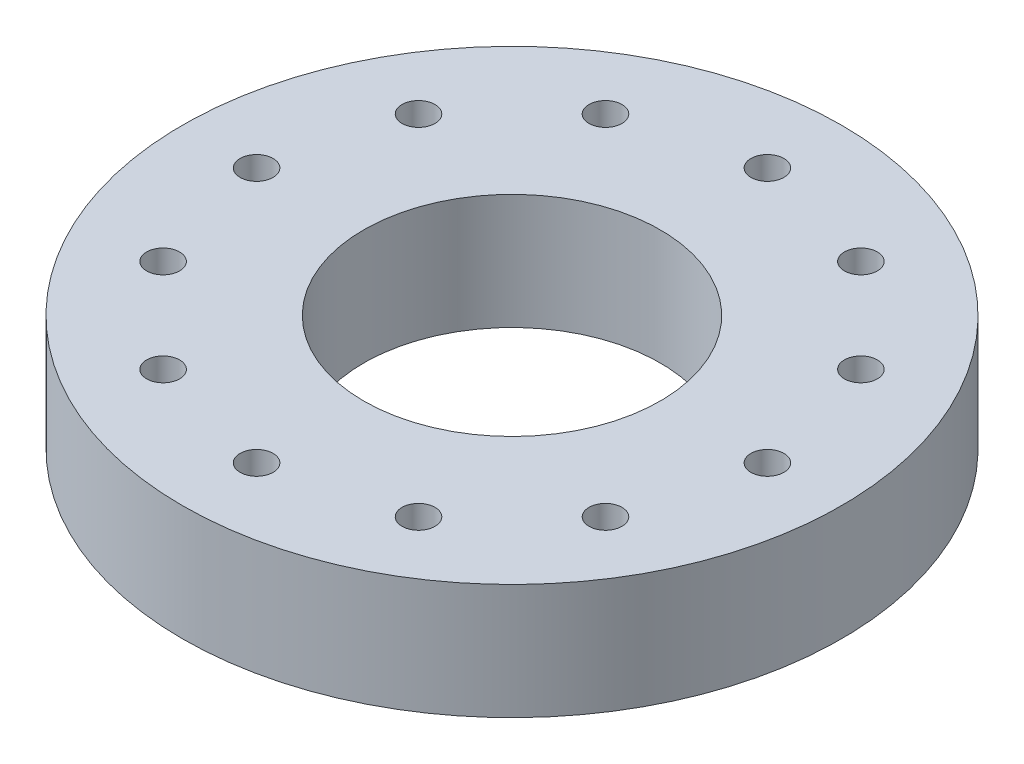
SolidWorks part; units mm, degrees
ref_plane "Front Plane" through (0, 0, 0) normal (0, 0, 1) x (1, 0, 0)
ref_plane "Top Plane" through (0, 0, 0) normal (0, 1, 0) x (1, 0, 0)
ref_plane "Right Plane" through (0, 0, 0) normal (1, 0, 0) x (0, 0, -1)
sketch "Sketch1" plane through (0, 0, 0) normal (0, 1, 0) x (1, 0, 0)
  circle A0 centre (0, 0) radius 20
  circle A1 centre (0, 0) radius 9
  circle A2 centre (0, 0) radius 15.5 construction
  circle A3 centre (0, 15.5) radius 1
  circle A4 centre (7.75, 13.4234) radius 1
  circle A5 centre (13.4234, 7.75) radius 1
  circle A6 centre (15.5, 0) radius 1
  circle A7 centre (13.4234, -7.75) radius 1
  circle A8 centre (7.75, -13.4234) radius 1
  circle A9 centre (0, -15.5) radius 1
  circle A10 centre (-7.75, -13.4234) radius 1
  circle A11 centre (-13.4234, -7.75) radius 1
  circle A12 centre (-15.5, 0) radius 1
  circle A13 centre (-13.4234, 7.75) radius 1
  circle A14 centre (-7.75, 13.4234) radius 1
  point P19 (0, 0)
  dimension "D1" = 40
  dimension "D2" = 18
  dimension "D3" = 31
  dimension "D4" = 2
  dimension "D5" = 12
extrude "Boss-Extrude1" add sketch "Sketch1" along normal blind 7
